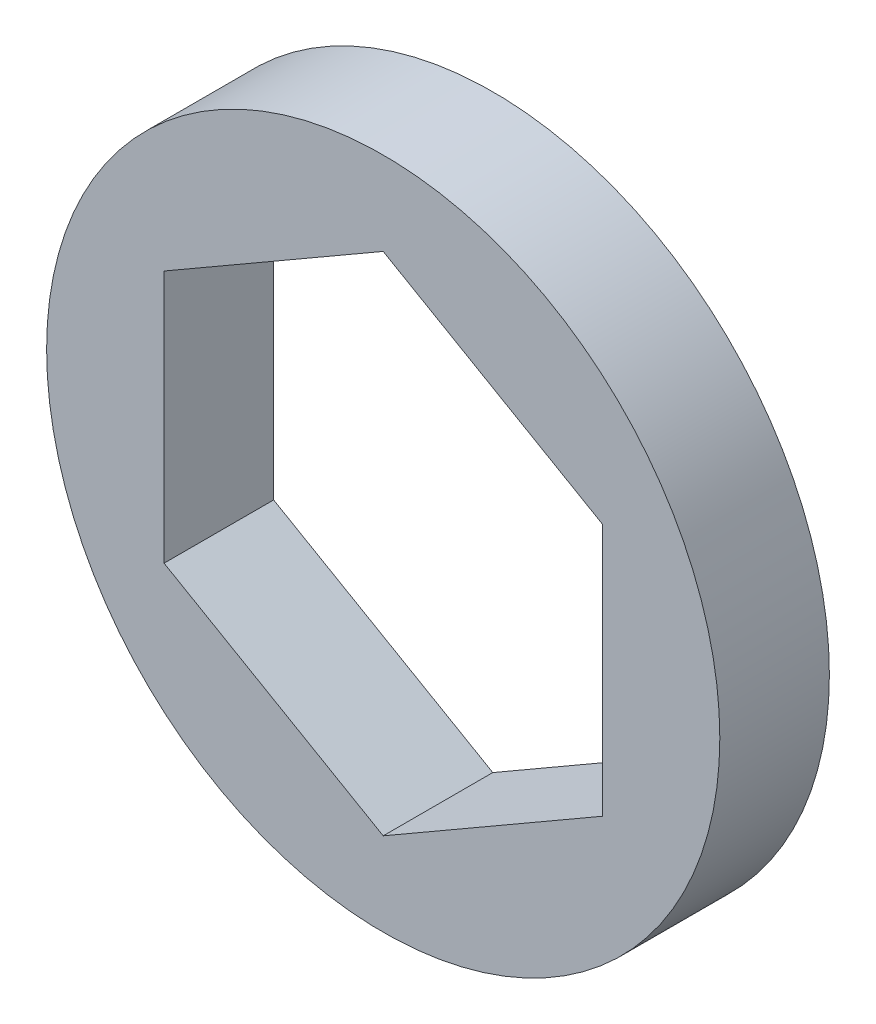
SolidWorks part; units mm, degrees
material "Delrin 2700 NC010, Low Viscosity Acetal Copolymer (SS)"
ref_plane "Front" through (0, 0, 0) normal (0, 0, 1) x (1, 0, 0)
ref_plane "Top" through (0, 0, 0) normal (0, 1, 0) x (1, 0, 0)
ref_plane "Right" through (0, 0, 0) normal (1, 0, 0) x (0, 0, -1)
sketch "Sketch1" plane through (0, 0, 0) normal (0, 0, 1) x (1, 0, 0)
  line L1 (-6.35, 3.6662) -> (-6.35, -3.6662)
  line L2 (-6.35, -3.6662) -> (0, -7.3323)
  line L3 (0, -7.3323) -> (6.35, -3.6662)
  line L4 (6.35, -3.6662) -> (6.35, 3.6662)
  line L5 (6.35, 3.6662) -> (0, 7.3323)
  line L6 (0, 7.3323) -> (-6.35, 3.6662)
  circle A0 centre (0, 0) radius 9.7536
  circle A1 centre (0, 0) radius 6.35 construction
  dimension "D1" = 19.5072
  dimension "D2" = 12.7
extrude "Spacer Boss" add sketch "Sketch1" along normal blind 3.175
equation "\"HS\"=1 / 2'Hex Size"
equation "\"OD\"=.768'Outer Diameter"
equation "\"L\"=1 / 8'Length"
equation "\"D1@Sketch1\"=\"OD\""
equation "\"D2@Sketch1\"=\"HS\""
equation "\"D1@Spacer Boss\" = \"L\""
